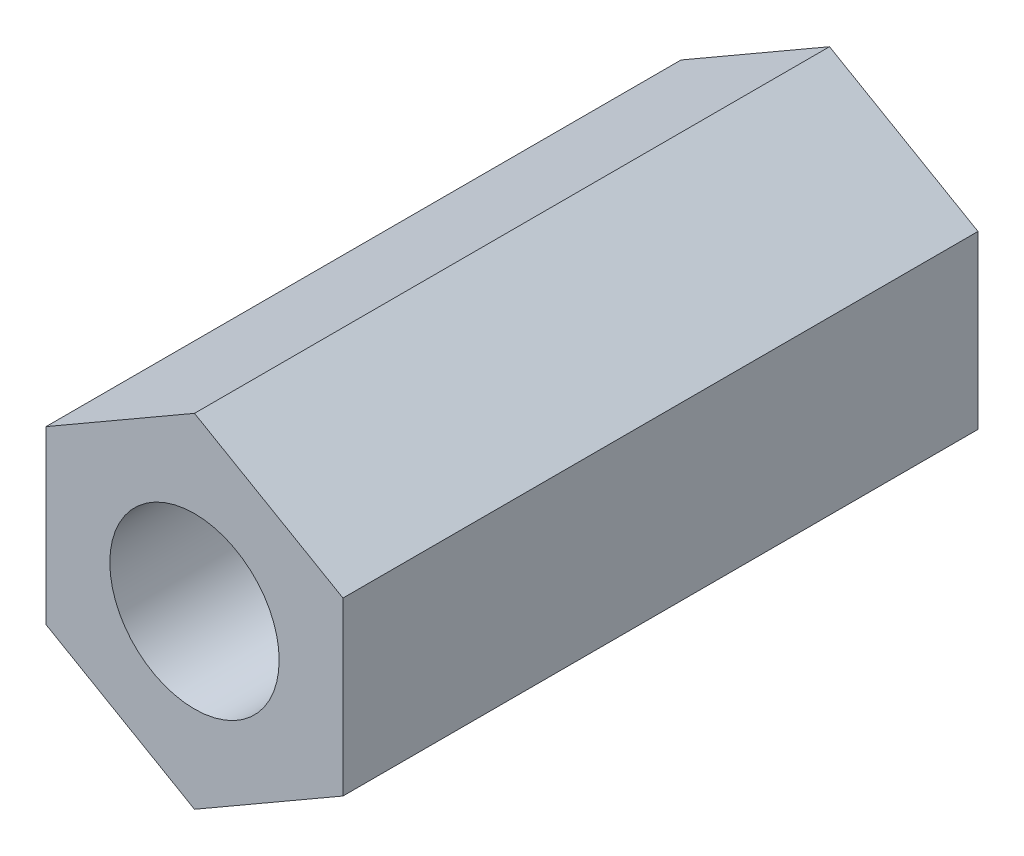
SolidWorks part; units mm, degrees
ref_plane "前视基准面" through (0, 0, 0) normal (0, 0, 1) x (1, 0, 0)
ref_plane "上视基准面" through (0, 0, 0) normal (0, 1, 0) x (1, 0, 0)
ref_plane "右视基准面" through (0, 0, 0) normal (1, 0, 0) x (0, 0, -1)
sketch "草图1" plane through (0, 0, 0) normal (0, 0, 1) x (1, 0, 0)
  line L0 (0, 0) -> (0, 4.05)
  line L1 (0, 4.05) -> (-3.5074, 2.025)
  line L2 (-3.5074, 2.025) -> (-3.5074, -2.025)
  line L3 (-3.5074, -2.025) -> (0, -4.05)
  line L4 (0, -4.05) -> (3.5074, -2.025)
  line L5 (3.5074, -2.025) -> (3.5074, 2.025)
  line L6 (3.5074, 2.025) -> (0, 4.05)
  circle A0 centre (0, 0) radius 3.5074 construction
  circle A1 centre (0, 0) radius 2
  dimension "D1" = 4
extrude "凸台-拉伸1" add sketch "草图1" along normal blind 15
